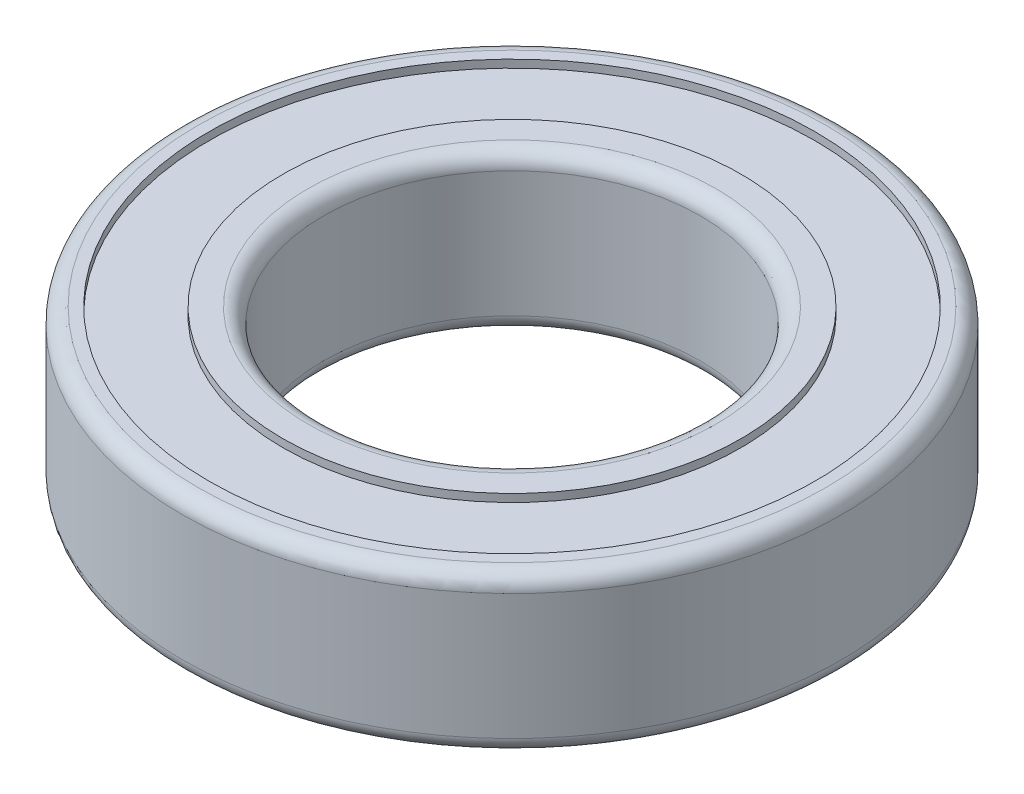
SolidWorks part; units mm, degrees
ref_plane "Ebene vorne" through (0, 0, 0) normal (0, 0, 1) x (1, 0, 0)
ref_plane "Ebene oben" through (0, 0, 0) normal (0, 1, 0) x (1, 0, 0)
ref_plane "Ebene rechts" through (0, 0, 0) normal (1, 0, 0) x (0, 0, -1)
sketch "Skizze1" plane through (0, 0, 0) normal (0, 0, 1) x (1, 0, 0)
  line L0 (0, 0) -> (0, -14365.7934) construction
  line L1 (6, 0) -> (7.3, 0)
  line L2 (7.3, 0) -> (7.3, 0.25)
  line L3 (7.3, 0.25) -> (9.65, 0.25)
  line L4 (9.65, 0.25) -> (9.65, 0)
  line L5 (9.65, 0) -> (10.5, 0)
  line L6 (10.5, 0) -> (10.5, 5)
  line L7 (10.5, 5) -> (9.65, 5)
  line L8 (9.65, 5) -> (9.65, 4.75)
  line L9 (9.65, 4.75) -> (7.3, 4.75)
  line L10 (7.3, 4.75) -> (7.3, 5)
  line L11 (7.3, 5) -> (6, 5)
  line L12 (6, 5) -> (6, 0)
  dimension "D1" = 12
  dimension "D2" = 21
  dimension "D3" = 19.3
  dimension "D4" = 14.6
  dimension "D5" = 5
  dimension "D6" = 4.5
  dimension "D7" = 0.25
revolve "Rotation1" add sketch "Skizze1" angle 360 about L0
fillet "Verrundung1" radius 0.5 4 edges at (0, 0, 10.5) (0, 5, 10.5) (0, 0, 6) (0, 5, 6)
